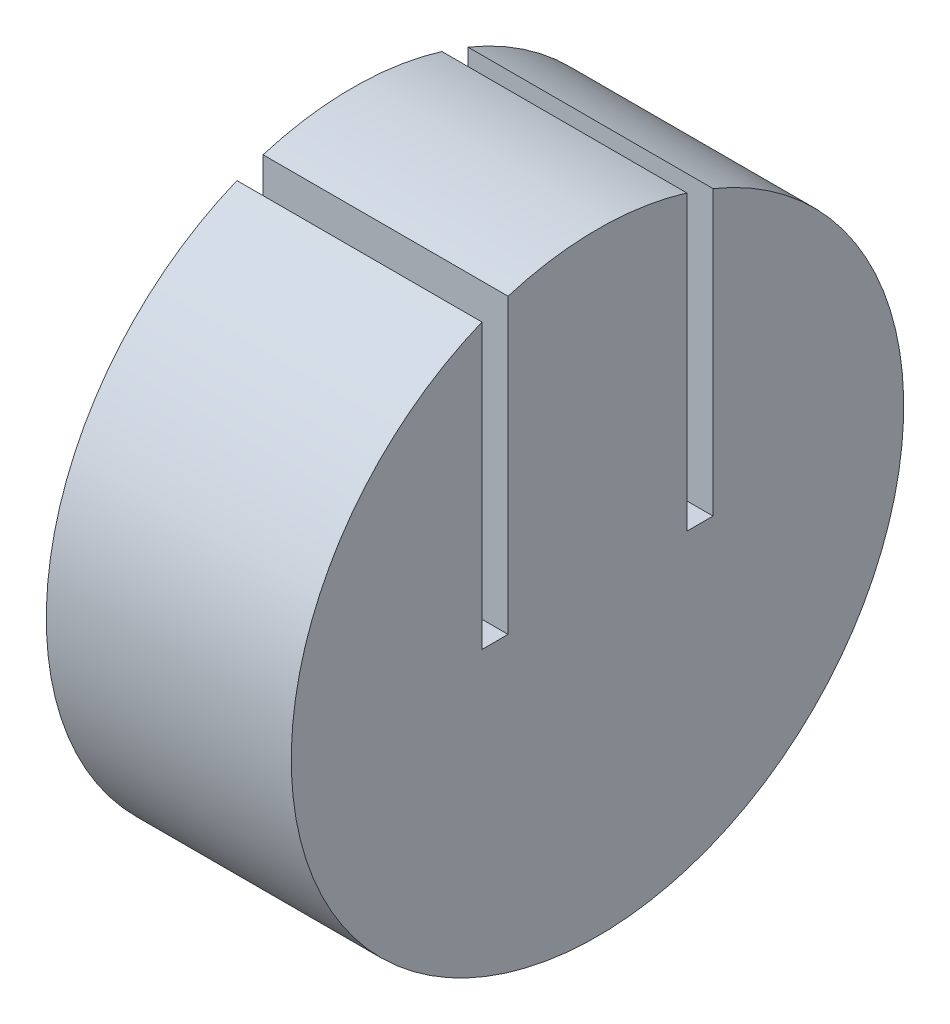
SolidWorks part; units mm, degrees
ref_plane "Front Plane" through (0, 0, 0) normal (0, 0, 1) x (1, 0, 0)
ref_plane "Top Plane" through (0, 0, 0) normal (0, 1, 0) x (1, 0, 0)
ref_plane "Right Plane" through (0, 0, 0) normal (1, 0, 0) x (0, 0, -1)
sketch "Sketch1" plane through (0, 0, 0) normal (1, 0, 0) x (0, 0, -1)
  line L0 (-2.7813, 0) -> (2.7813, 0) construction
  line L1 (-3.5941, 9.1099) -> (-2.7813, 9.1099)
  line L2 (-3.5941, 9.1099) -> (-3.5941, 0)
  line L3 (-3.5941, 0) -> (-2.7813, 0)
  line L4 (-2.7813, 9.1099) -> (-2.7813, 0)
  line L5 (2.7813, 0) -> (3.5941, 0)
  line L6 (2.7813, 0) -> (2.7813, 9.1099)
  line L7 (2.7813, 9.1099) -> (3.5941, 9.1099)
  line L8 (3.5941, 0) -> (3.5941, 9.1099)
  circle A0 centre (0, 0) radius 9.525
  point P11 (0, 0)
  dimension "D1" = 0.8128
  dimension "D3" = 19.05
  dimension "D2" = 5.5626
extrude "Boss-Extrude1" add sketch "Sketch1" along normal blind 7.62 contours L4 L0 L6 A0 | L0 L3 L2 A0 L8 L5
